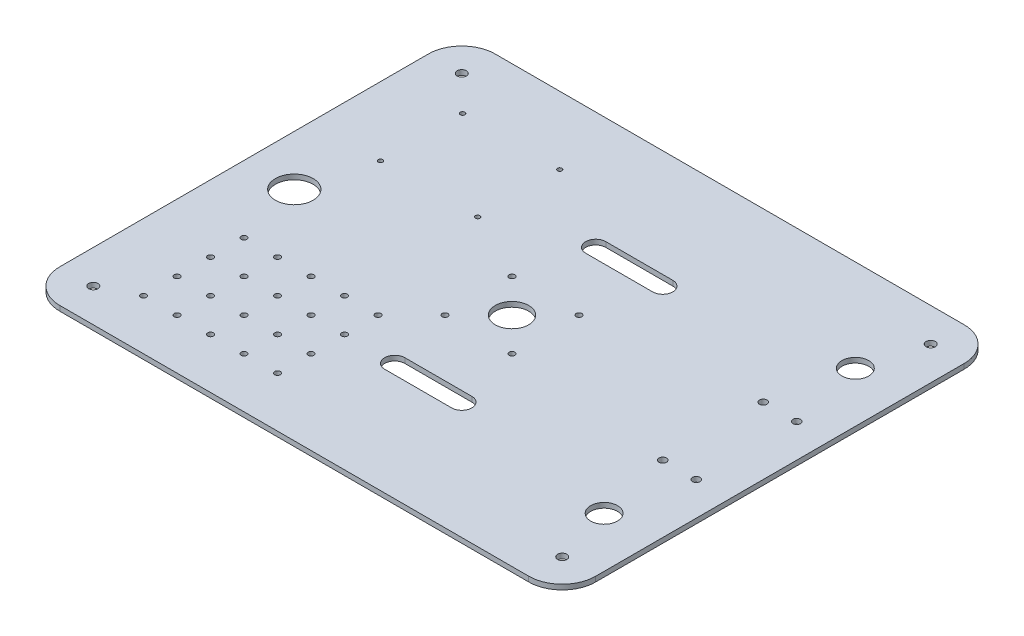
SolidWorks part; units mm, degrees
material "6061-T6 (SS)"
ref_plane "Front Plane" through (0, 0, 0) normal (0, 0, 1) x (1, 0, 0)
ref_plane "Top Plane" through (0, 0, 0) normal (0, 1, 0) x (1, 0, 0)
ref_plane "Right Plane" through (0, 0, 0) normal (1, 0, 0) x (0, 0, -1)
sketch "SK_Deck" plane through (0, 0, 0) normal (0, 1, 0) x (1, 0, 0)
  line L0 (160, -110) -> (160, 110)
  line L1 (140, 130) -> (-140, 130)
  line L2 (-160, 110) -> (-160, -110)
  line L3 (-140, -130) -> (140, -130)
  arc A0 (160, 110) -> (140, 130) centre (140, 110) ccw
  arc A1 (-140, 130) -> (-160, 110) centre (-140, 110) ccw
  arc A2 (-160, -110) -> (-140, -130) centre (-140, -110) ccw
  arc A3 (140, -130) -> (160, -110) centre (140, -110) ccw
extrude "Deck" add sketch "SK_Deck" along normal blind 3
sketch "SK_DeckPosts_M5" plane through (0, 0, 0) normal (0, 1, 0) x (1, 0, 0)
  circle A0 centre (140, 110) radius 2.75
  circle A1 centre (140, -110) radius 2.75
  circle A2 centre (-140, 110) radius 2.75
  circle A3 centre (-140, -110) radius 2.75
extrude "Cut_DeckPosts_M5" cut sketch "SK_DeckPosts_M5" against normal through all and the other way through all
sketch "SK_LidarMount" plane through (0, 0, 0) normal (0, 1, 0) x (1, 0, 0)
  circle A0 centre (20, 20) radius 1.7
  circle A1 centre (20, -20) radius 1.7
  circle A2 centre (-20, 20) radius 1.7
  circle A3 centre (-20, -20) radius 1.7
  circle A4 centre (0, 0) radius 10
extrude "Cut_LidarMount" cut sketch "SK_LidarMount" against normal through all and the other way through all
sketch "SK_Pi5_M2p5" plane through (0, 0, 0) normal (0, 1, 0) x (1, 0, 0)
  circle A0 centre (-119, 40.5) radius 1.35
  circle A1 centre (-119, 89.5) radius 1.35
  circle A2 centre (-61, 40.5) radius 1.35
  circle A3 centre (-61, 89.5) radius 1.35
extrude "Cut_Pi5_M2p5" cut sketch "SK_Pi5_M2p5" against normal through all and the other way through all
sketch "SK_DeckGrid_M3" plane through (0, 0, 0) normal (0, 1, 0) x (1, 0, 0)
  circle A0 centre (-120, -40) radius 1.7
  circle A1 centre (-120, -60) radius 1.7
  circle A2 centre (-120, -80) radius 1.7
  circle A3 centre (-120, -100) radius 1.7
  circle A4 centre (-100, -40) radius 1.7
  circle A5 centre (-100, -60) radius 1.7
  circle A6 centre (-100, -80) radius 1.7
  circle A7 centre (-100, -100) radius 1.7
  circle A8 centre (-80, -40) radius 1.7
  circle A9 centre (-80, -60) radius 1.7
  circle A10 centre (-80, -80) radius 1.7
  circle A11 centre (-80, -100) radius 1.7
  circle A12 centre (-60, -40) radius 1.7
  circle A13 centre (-60, -60) radius 1.7
  circle A14 centre (-60, -80) radius 1.7
  circle A15 centre (-60, -100) radius 1.7
  circle A16 centre (-40, -40) radius 1.7
  circle A17 centre (-40, -60) radius 1.7
  circle A18 centre (-40, -80) radius 1.7
  circle A19 centre (-40, -100) radius 1.7
extrude "Cut_DeckGrid_M3" cut sketch "SK_DeckGrid_M3" against normal through all and the other way through all
sketch "SK_EStop_22mm" plane through (0, 0, 0) normal (0, 1, 0) x (1, 0, 0)
  circle A0 centre (-130, 0) radius 11.25
extrude "Cut_EStop_22mm" cut sketch "SK_EStop_22mm" against normal through all and the other way through all
sketch "SK_CameraMount_M4" plane through (0, 0, 0) normal (0, 1, 0) x (1, 0, 0)
  circle A0 centre (120, 30) radius 2.25
  circle A1 centre (120, -30) radius 2.25
  circle A2 centre (140, 30) radius 2.25
  circle A3 centre (140, -30) radius 2.25
extrude "Cut_CameraMount_M4" cut sketch "SK_CameraMount_M4" against normal through all and the other way through all
sketch "SK_IndicatorLights" plane through (0, 0, 0) normal (0, 1, 0) x (1, 0, 0)
  circle A0 centre (130, 75) radius 8
  circle A1 centre (130, -75) radius 8
extrude "Cut_IndicatorLights_16mm" cut sketch "SK_IndicatorLights" against normal through all and the other way through all
sketch "SK_DeckPassThru" plane through (0, 0, 0) normal (0, 1, 0) x (1, 0, 0)
  line L0 (-10, 66) -> (30, 66)
  line L1 (30, 54) -> (-10, 54)
  line L2 (-10, -54) -> (30, -54)
  line L3 (30, -66) -> (-10, -66)
  arc A0 (30, 66) -> (30, 54) centre (30, 60) cw
  arc A1 (-10, 54) -> (-10, 66) centre (-10, 60) cw
  arc A2 (30, -54) -> (30, -66) centre (30, -60) cw
  arc A3 (-10, -66) -> (-10, -54) centre (-10, -60) cw
extrude "Cut_DeckPassThru" cut sketch "SK_DeckPassThru" against normal through all and the other way through all
